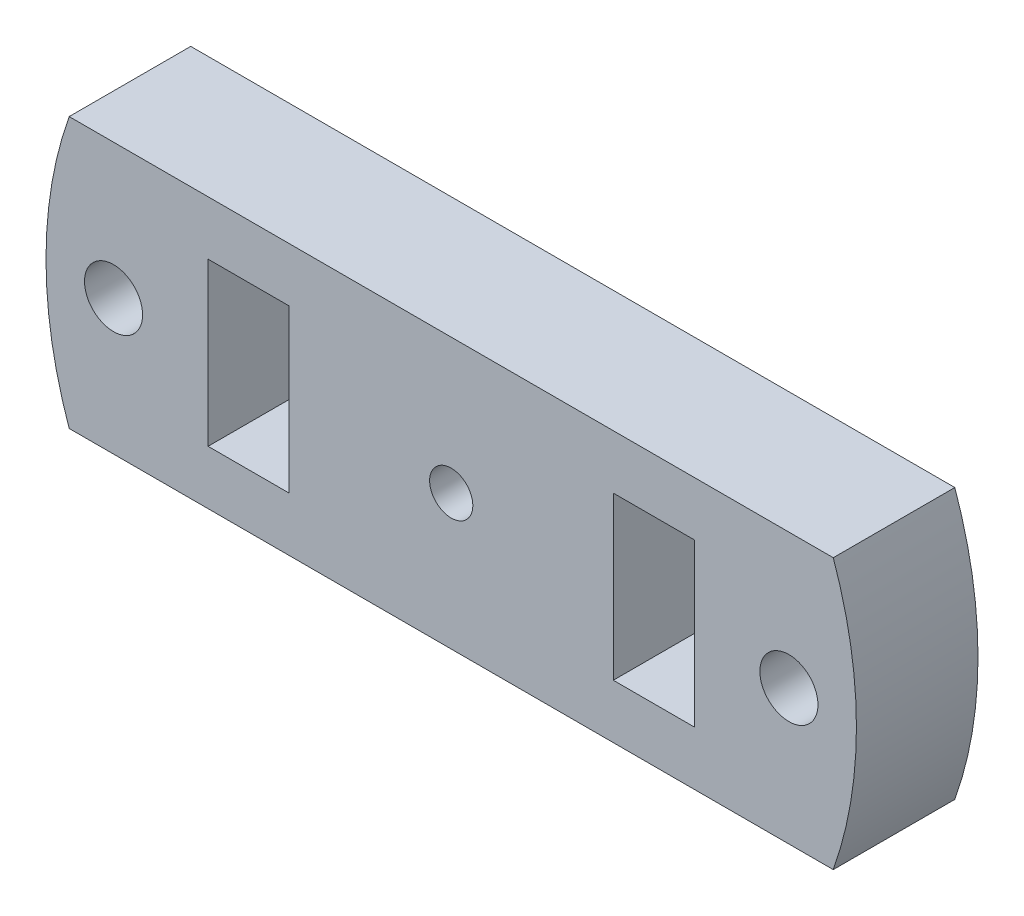
SolidWorks part; units mm, degrees
ref_plane "Plan de face" through (0, 0, 0) normal (0, 0, 1) x (1, 0, 0)
ref_plane "Plan de dessus" through (0, 0, 0) normal (0, 1, 0) x (1, 0, 0)
ref_plane "Plan de droite" through (0, 0, 0) normal (1, 0, 0) x (0, 0, -1)
sketch "Esquisse1" plane through (0, 0, 0) normal (0, 0, 1) x (1, 0, 0)
  line L0 (0, 0) -> (30, 0) construction
  line L1 (0, 0) -> (-30, 0) construction
  line L2 (-18, -6) -> (-12, -6)
  line L3 (12, -6) -> (18, -6)
  line L4 (12, 6) -> (18, 6)
  line L5 (-18, 6) -> (-12, 6)
  line L7 (0, -10) -> (-28.2843, -10)
  line L8 (0, -10) -> (28.2843, -10)
  line L9 (0, 10) -> (-28.2843, 10)
  line L10 (0, 10) -> (28.2843, 10)
  line L14 (-18, 6) -> (-18, -6)
  line L16 (-12, 6) -> (-12, -6)
  line L18 (12, 6) -> (12, -6)
  line L20 (18, 6) -> (18, -6)
  arc A0 (-28.2843, 10) -> (-28.2843, -10) centre (0, 0) ccw
  circle A1 centre (-25, 0) radius 2.15
  circle A2 centre (25, 0) radius 2.15
  circle A3 centre (0, 0) radius 8 construction
  arc A4 (28.2843, -10) -> (28.2843, 10) centre (0, 0) ccw
  point P3 (-39.2859, 0)
  point P4 (45.0769, 0)
  point P5 (0, 15)
  point P6 (45.0769, 15)
  point P7 (-39.2859, 15)
  point P8 (0, -15)
  point P9 (45.0769, -15)
  point P10 (-39.2859, -15)
  dimension "D1" = 60
  dimension "D4" = 50
  dimension "D5" = 4.3
  dimension "D6" = 4.3
  dimension "D8" = 16
  dimension "D7" = 5
  dimension "D11" = 12
  dimension "D12" = 12
extrude "Boss.-Extru.1" add sketch "Esquisse1" along normal blind 9
sketch "Esquisse2" plane through (0, 0, 0) normal (0, 0, -1) x (-1, 0, 0)
  circle A0 centre (0, 0) radius 8
  dimension "D1" = 16
extrude "Enlèv. mat.-Extru.1" cut sketch "Esquisse2" against normal blind 5
sketch "Esquisse3" plane through (0, 0, 9) normal (0, 0, 1) x (1, 0, 0)
  circle A0 centre (0, 0) radius 1.6
  dimension "D1" = 3.2
extrude "Enlèv. mat.-Extru.2" cut sketch "Esquisse3" against normal through all contours A0
